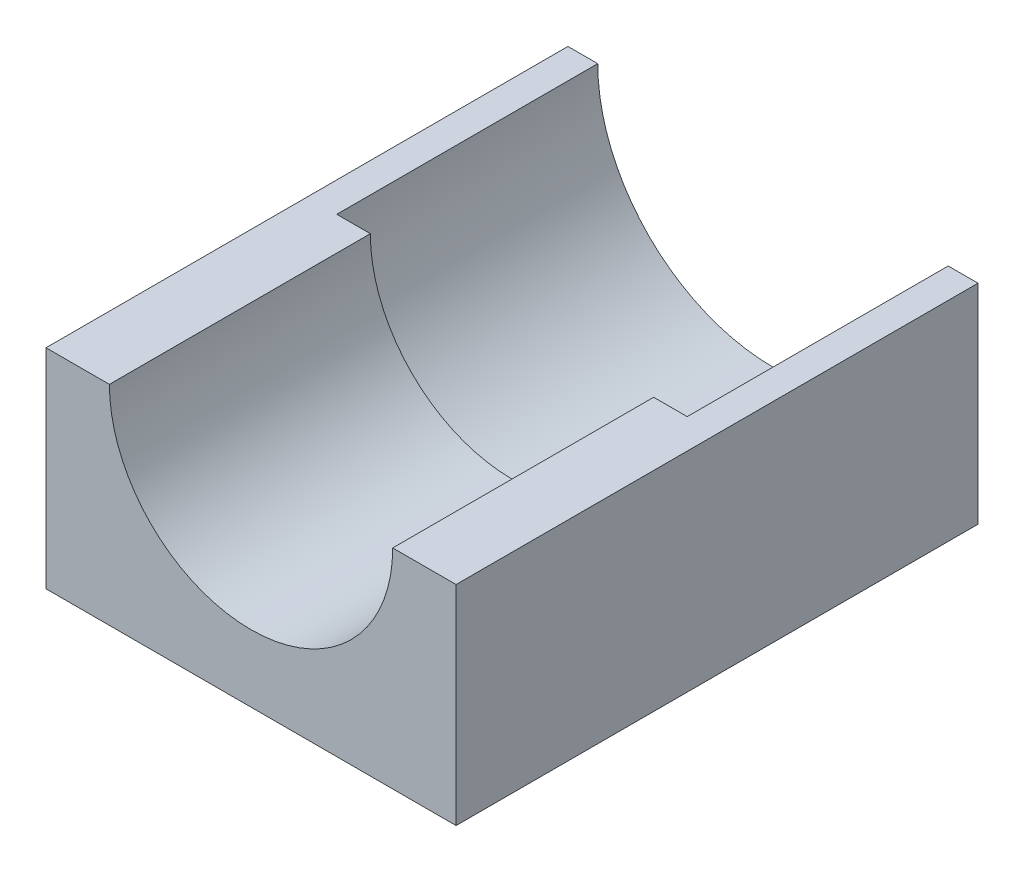
SolidWorks part; units mm, degrees
ref_plane "Front Plane" through (0, 0, 0) normal (0, 0, 1) x (1, 0, 0)
ref_plane "Top Plane" through (0, 0, 0) normal (0, 1, 0) x (1, 0, 0)
ref_plane "Right Plane" through (0, 0, 0) normal (1, 0, 0) x (0, 0, -1)
sketch "Sketch2" plane through (0, 0, 0) normal (0, 0, 1) x (1, 0, 0)
  line L0 (48.7489, 15.9323) -> (44.7489, 15.9323)
  line L1 (44.7489, 15.9323) -> (44.7489, -12.0677)
  line L2 (44.7489, -12.0677) -> (99.7489, -12.0677)
  line L3 (99.7489, -12.0677) -> (99.7489, 15.9323)
  line L4 (99.7489, 15.9323) -> (95.7489, 15.9323)
  arc A0 (95.7489, 15.9323) -> (48.7489, 15.9323) centre (72.2489, 15.9323) cw
  dimension "D1" = 4
  dimension "D2" = 4
  dimension "D3" = 28
  dimension "D4" = 55
  dimension "D5" = 28
extrude "Boss-Extrude1" add sketch "Sketch2" along normal blind 35
sketch "Sketch3" plane through (0, 0, 35) normal (0, 0, 1) x (1, 0, 0)
  line L0 (91.2489, 15.9323) -> (99.7489, 15.9323)
  line L1 (99.7489, 15.9323) -> (99.7489, -12.0677)
  line L2 (99.7489, -12.0677) -> (44.7489, -12.0677)
  line L3 (44.7489, -12.0677) -> (44.7489, 15.9323)
  line L4 (44.7489, 15.9323) -> (53.2489, 15.9323)
  arc A0 (91.2489, 15.9323) -> (53.2489, 15.9323) centre (72.2489, 15.9323) cw
  circle A1 centre (72.2489, 15.9323) radius 19 construction
  dimension "D1" = 0
extrude "Boss-Extrude2" add sketch "Sketch3" along normal blind 35
